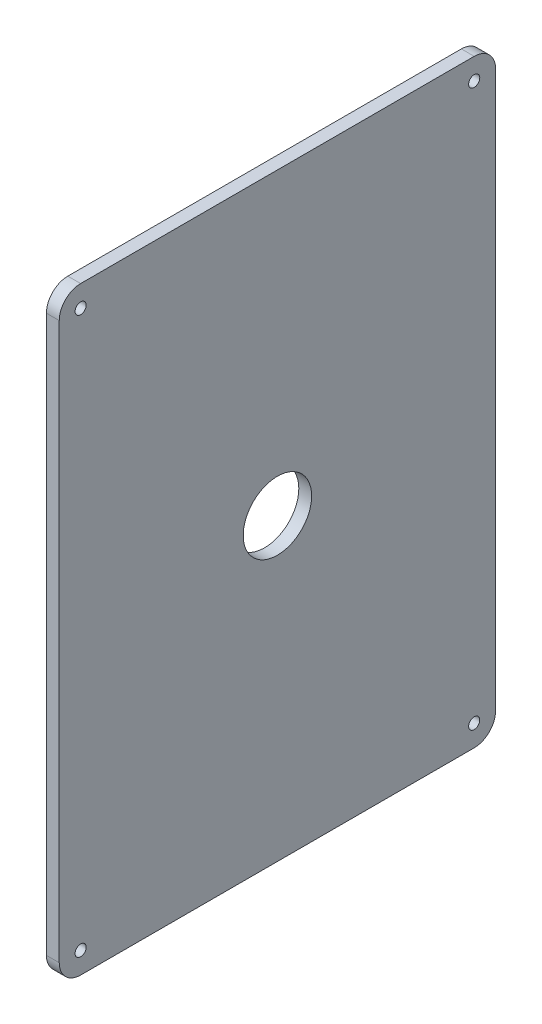
SolidWorks part; units mm, degrees
ref_plane "Front Plane" through (0, 0, 0) normal (0, 0, 1) x (1, 0, 0)
ref_plane "Top Plane" through (0, 0, 0) normal (0, 1, 0) x (1, 0, 0)
ref_plane "Right Plane" through (0, 0, 0) normal (1, 0, 0) x (0, 0, -1)
sketch "Sketch1" plane through (0, 0, 0) normal (1, 0, 0) x (0, 0, -1)
  line L1 (0, 0) -> (102, 0)
  line L2 (0, 0) -> (0, -140)
  line L3 (0, -140) -> (102, -140)
  line L4 (102, 0) -> (102, -140)
  dimension "D1" = 140
  dimension "D2" = 102
extrude "Boss-Extrude1" add sketch "Sketch1" along normal blind 3
fillet "Fillet1" radius 5 4 edges at (1.5, 0, 0) (1.5, 0, -102) (1.5, -140, -102) (1.5, -140, 0)
sketch "Sketch2" plane through (3, 0, 0) normal (1, 0, 0) x (0, 0, -1)
  line L0 (100.5355, -138.5355) -> (1.4645, -1.4645)
  line L1 (1.4645, -138.5355) -> (100.5355, -1.4645)
  arc A0 (97, -140) -> (102, -135) centre (97, -135) ccw construction
  arc A1 (5, 0) -> (0, -5) centre (5, -5) ccw construction
  arc A2 (0, -135) -> (5, -140) centre (5, -135) ccw construction
  arc A3 (102, -5) -> (97, 0) centre (97, -5) ccw construction
  circle A4 centre (51, -70) radius 8
  dimension "D1" = 16
extrude "Cut-Extrude1" cut sketch "Sketch2" against normal blind 3 contours L0 A4 L1 | L1 A4 L0 | L0 A4 L1 | L1 A4 L0
sketch "Sketch3" plane through (3, 0, 0) normal (1, 0, 0) x (0, 0, -1)
  line L0 (102, -135) -> (102, -5) construction
  line L1 (5, -140) -> (97, -140) construction
  line L2 (0, -5) -> (0, -135) construction
  line L3 (97, 0) -> (5, 0) construction
  circle A0 centre (5, -135) radius 1.3
  circle A1 centre (5, -5) radius 1.3
  circle A2 centre (97, -5) radius 1.3
  circle A3 centre (97, -135) radius 1.3
  dimension "D1" = 2.6
  dimension "D2" = 2.6
  dimension "D3" = 2.6
  dimension "D4" = 2.6
  dimension "D5" = 5
  dimension "D6" = 5
  dimension "D7" = 5
  dimension "D8" = 5
  dimension "D9" = 5
  dimension "D10" = 5
  dimension "D11" = 5
  dimension "D12" = 5
extrude "Cut-Extrude2" cut sketch "Sketch3" against normal blind 100
